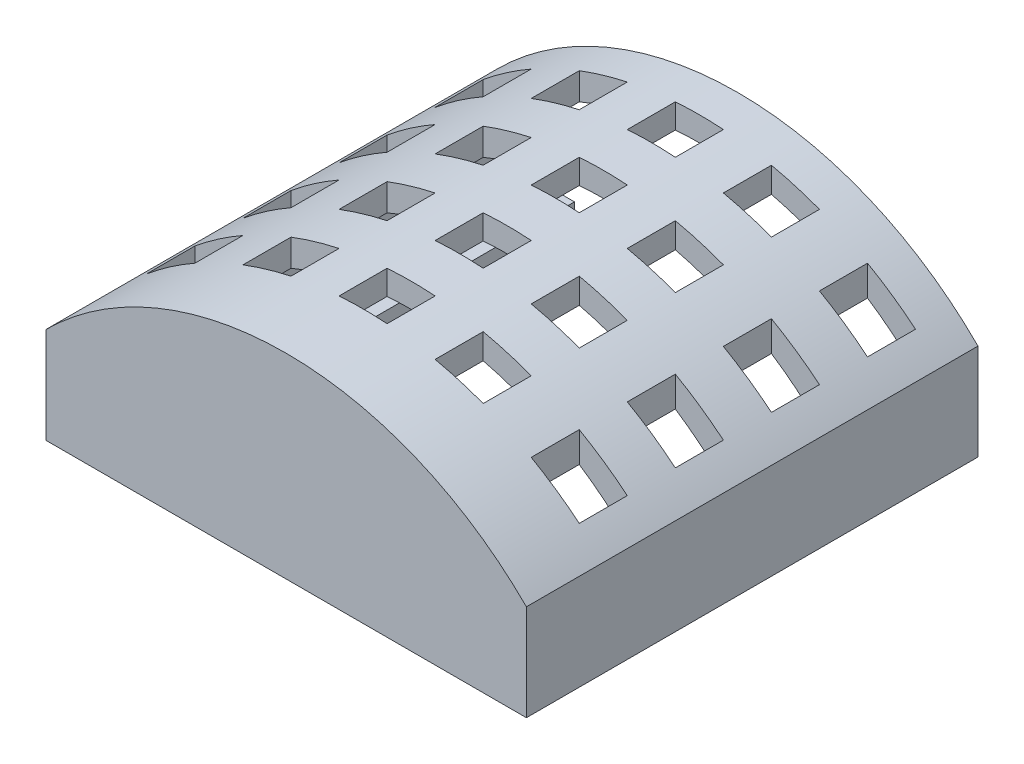
SolidWorks part; units mm, degrees
ref_plane "Спереди" through (0, 0, 0) normal (0, 0, 1) x (1, 0, 0)
ref_plane "Сверху" through (0, 0, 0) normal (0, 1, 0) x (1, 0, 0)
ref_plane "Справа" through (0, 0, 0) normal (1, 0, 0) x (0, 0, -1)
sketch "Эскиз1" plane through (0, 0, 0) normal (0, 0, 1) x (1, 0, 0)
  line L0 (0, 0) -> (0, 6)
  line L1 (0, 0) -> (0, -4)
  line L2 (0, -4) -> (8, -4)
  line L3 (50, 0) -> (50, -4)
  line L4 (50, -4) -> (42, -4)
  line L5 (50, 0) -> (50, 6)
  line L6 (8, -4) -> (8, -2)
  line L7 (2.5, 0) -> (2.5, -2)
  line L8 (2.5, -2) -> (8, -2)
  line L9 (47.5, 0) -> (47.5, -2)
  line L10 (47.5, -2) -> (42, -2)
  line L11 (42, -2) -> (42, -4)
  line L12 (2.5, 0) -> (2.5, 4.5)
  line L13 (47.5, 0) -> (47.5, 4.5)
  arc A0 (0, 6) -> (50, 6) centre (25, -19) cw
  arc A1 (2.5, 4.5) -> (47.5, 4.5) centre (25, -18) cw
extrude "Бобышка-Вытянуть1" add sketch "Эскиз1" along normal blind 45
sketch "Эскиз3" plane through (0, 0, 45) normal (0, 0, 1) x (1, 0, 0)
  line L1 (0, -4) -> (50, -4)
  line L2 (0, -4) -> (0, 6)
  line L4 (50, -4) -> (50, 6)
  arc A0 (0, 6) -> (50, 6) centre (25, -19) cw
extrude "Бобышка-Вытянуть2" add sketch "Эскиз3" along normal blind 2
ref_plane "Плоскость1" through (0, 4, 0) normal (0, 1, 0) x (1, 0, 0)
sketch "Эскиз5" plane through (0, 4, 0) normal (0, 1, 0) x (1, 0, 0)
  line L1 (12.5, -4) -> (17.5, -4)
  line L2 (12.5, -4) -> (12.5, -9)
  line L3 (12.5, -9) -> (17.5, -9)
  line L4 (17.5, -4) -> (17.5, -9)
  line L5 (2.5, -4) -> (7.5, -4)
  line L6 (2.5, -4) -> (2.5, -9)
  line L7 (2.5, -9) -> (7.5, -9)
  line L8 (7.5, -4) -> (7.5, -9)
  line L9 (22.5, -4) -> (27.5, -4)
  line L10 (22.5, -4) -> (22.5, -9)
  line L11 (22.5, -9) -> (27.5, -9)
  line L12 (27.5, -4) -> (27.5, -9)
  line L13 (32.5, -4) -> (37.5, -4)
  line L14 (32.5, -4) -> (32.5, -9)
  line L15 (32.5, -9) -> (37.5, -9)
  line L16 (37.5, -4) -> (37.5, -9)
  line L17 (42.5, -4) -> (47.5, -4)
  line L18 (42.5, -4) -> (42.5, -9)
  line L19 (42.5, -9) -> (47.5, -9)
  line L20 (47.5, -4) -> (47.5, -9)
  line L22 (12.5, -14) -> (17.5, -14)
  line L23 (12.5, -14) -> (12.5, -19)
  line L24 (12.5, -19) -> (17.5, -19)
  line L25 (17.5, -14) -> (17.5, -19)
  line L26 (2.5, -14) -> (7.5, -14)
  line L27 (2.5, -14) -> (2.5, -19)
  line L28 (2.5, -19) -> (7.5, -19)
  line L29 (7.5, -14) -> (7.5, -19)
  line L30 (22.5, -14) -> (27.5, -14)
  line L31 (22.5, -14) -> (22.5, -19)
  line L32 (22.5, -19) -> (27.5, -19)
  line L33 (27.5, -14) -> (27.5, -19)
  line L34 (32.5, -14) -> (37.5, -14)
  line L35 (32.5, -14) -> (32.5, -19)
  line L36 (32.5, -19) -> (37.5, -19)
  line L37 (37.5, -14) -> (37.5, -19)
  line L38 (42.5, -14) -> (47.5, -14)
  line L39 (42.5, -14) -> (42.5, -19)
  line L40 (42.5, -19) -> (47.5, -19)
  line L41 (47.5, -14) -> (47.5, -19)
  line L43 (12.5, -24) -> (17.5, -24)
  line L44 (12.5, -24) -> (12.5, -29)
  line L45 (12.5, -29) -> (17.5, -29)
  line L46 (17.5, -24) -> (17.5, -29)
  line L47 (2.5, -24) -> (7.5, -24)
  line L48 (2.5, -24) -> (2.5, -29)
  line L49 (2.5, -29) -> (7.5, -29)
  line L50 (7.5, -24) -> (7.5, -29)
  line L51 (22.5, -24) -> (27.5, -24)
  line L52 (22.5, -24) -> (22.5, -29)
  line L53 (22.5, -29) -> (27.5, -29)
  line L54 (27.5, -24) -> (27.5, -29)
  line L55 (32.5, -24) -> (37.5, -24)
  line L56 (32.5, -24) -> (32.5, -29)
  line L57 (32.5, -29) -> (37.5, -29)
  line L58 (37.5, -24) -> (37.5, -29)
  line L59 (42.5, -24) -> (47.5, -24)
  line L60 (42.5, -24) -> (42.5, -29)
  line L61 (42.5, -29) -> (47.5, -29)
  line L62 (47.5, -24) -> (47.5, -29)
  line L64 (12.5, -34) -> (17.5, -34)
  line L65 (12.5, -34) -> (12.5, -39)
  line L66 (12.5, -39) -> (17.5, -39)
  line L67 (17.5, -34) -> (17.5, -39)
  line L68 (2.5, -34) -> (7.5, -34)
  line L69 (2.5, -34) -> (2.5, -39)
  line L70 (2.5, -39) -> (7.5, -39)
  line L71 (7.5, -34) -> (7.5, -39)
  line L72 (22.5, -34) -> (27.5, -34)
  line L73 (22.5, -34) -> (22.5, -39)
  line L74 (22.5, -39) -> (27.5, -39)
  line L75 (27.5, -34) -> (27.5, -39)
  line L76 (32.5, -34) -> (37.5, -34)
  line L77 (32.5, -34) -> (32.5, -39)
  line L78 (32.5, -39) -> (37.5, -39)
  line L79 (37.5, -34) -> (37.5, -39)
  line L80 (42.5, -34) -> (47.5, -34)
  line L81 (42.5, -34) -> (42.5, -39)
  line L82 (42.5, -39) -> (47.5, -39)
  line L83 (47.5, -34) -> (47.5, -39)
  dimension "D1" = 5
  dimension "D2" = 4
extrude "Вырез-Вытянуть1" cut sketch "Эскиз5" along normal blind 46
